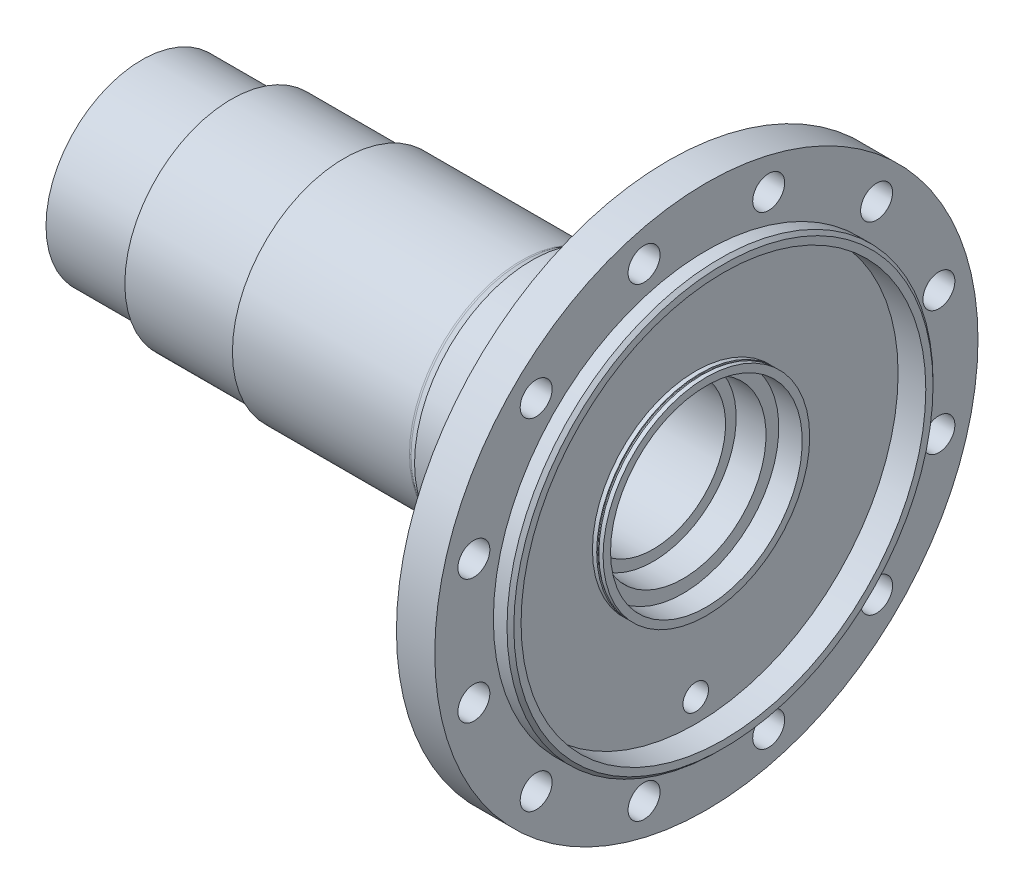
SolidWorks part; units mm, degrees
ref_plane "Спереди" through (0, 0, 0) normal (0, 0, 1) x (1, 0, 0)
ref_plane "Сверху" through (0, 0, 0) normal (0, 1, 0) x (1, 0, 0)
ref_plane "Справа" through (0, 0, 0) normal (1, 0, 0) x (0, 0, -1)
sketch "Эскиз1" plane through (0, 0, 0) normal (0, 0, 1) x (1, 0, 0)
  line L0 (0, 0) -> (273, 0)
  line L1 (0, 0) -> (0, 45)
  line L2 (0, 45) -> (42, 45)
  line L3 (42, 45) -> (42, 50)
  line L4 (42, 50) -> (95, 50)
  line L5 (95, 50) -> (95, 52.5)
  line L6 (95, 52.5) -> (178.134, 52.5)
  line L7 (179.134, 52.7679) -> (183, 55)
  line L8 (183, 55) -> (213, 55)
  line L9 (215, 57) -> (215, 60.7679)
  line L10 (215, 60.7679) -> (218, 62.5)
  line L11 (218, 62.5) -> (237, 62.5)
  line L12 (239, 64.5) -> (239, 65.5)
  line L13 (239, 65.5) -> (240.4142, 66.9142)
  line L14 (241, 68.3284) -> (241, 78)
  line L15 (241, 78) -> (244.4142, 81.4142)
  line L16 (245, 82.8284) -> (245, 92)
  line L17 (245, 92) -> (246.4142, 93.4142)
  line L18 (247, 94.8284) -> (247, 127.5)
  line L19 (247, 127.5) -> (265, 127.5)
  line L20 (265, 127.5) -> (265, 100)
  line L21 (265, 100) -> (271.4, 100)
  line L22 (271.4, 100) -> (273, 98.4)
  line L23 (273, 98.4) -> (273, 0)
  arc A0 (178.134, 52.5) -> (179.134, 52.7679) centre (178.134, 54.5) ccw
  arc A1 (213, 55) -> (215, 57) centre (213, 57) ccw
  arc A2 (237, 62.5) -> (239, 64.5) centre (237, 64.5) ccw
  arc A3 (240.4142, 66.9142) -> (241, 68.3284) centre (239, 68.3284) ccw
  arc A4 (244.4142, 81.4142) -> (245, 82.8284) centre (243, 82.8284) ccw
  arc A5 (246.4142, 93.4142) -> (247, 94.8284) centre (245, 94.8284) ccw
revolve "Повернуть1" add sketch "Эскиз1" angle 360 about L0
sketch "Эскиз2" plane through (0, 0, 0) normal (0, 0, 1) x (1, 0, 0)
  line L0 (0, 0) -> (273, 0)
  line L1 (0, 0) -> (0, 32.7321)
  line L2 (0, 32.7321) -> (3, 31)
  line L3 (3, 31) -> (203.5, 31)
  line L4 (203.5, 31) -> (203.5, 34)
  line L5 (203.5, 34) -> (240, 34)
  line L6 (240, 34) -> (240, 39)
  line L7 (240, 39) -> (254, 39)
  line L8 (254, 39) -> (254, 45)
  line L9 (254, 45) -> (265, 45)
  line L10 (265, 45) -> (265, 95)
  line L11 (265, 95) -> (273, 95)
  line L12 (273, 95) -> (273, 0)
revolve "Вырез-Повернуть1" cut sketch "Эскиз2" angle 360 about L0
sketch "Эскиз3" plane through (0, 0, 0) normal (0, 0, 1) x (1, 0, 0)
  line L0 (0, 0) -> (273, 0) construction
  line L1 (260, 48.5) -> (262, 48.5)
  line L2 (262, 48.5) -> (262, 95)
  line L3 (262, 95) -> (260, 95)
  line L4 (260, 95) -> (260, 48.5)
revolve "Rear_recess_left" cut sketch "Эскиз3" angle 360 about L0
sketch "Эскиз4" plane through (0, 0, 0) normal (0, 0, 1) x (1, 0, 0)
  line L0 (0, 0) -> (273, 0) construction
  line L1 (263, 48) -> (263, 95)
  line L2 (263, 95) -> (262, 95)
  line L3 (262, 95) -> (262, 48)
  arc A0 (262, 48) -> (262.5, 47.5) centre (262.5, 48) ccw
  arc A1 (262.5, 47.5) -> (263, 48) centre (262.5, 48) ccw
revolve "Collar_groove_nominal" cut sketch "Эскиз4" angle 360 about L0
sketch "Эскиз5" plane through (0, 0, 0) normal (0, 0, 1) x (1, 0, 0)
  line L0 (0, 0) -> (273, 0) construction
  line L1 (263, 48.5) -> (265, 48.5)
  line L2 (265, 48.5) -> (265, 95)
  line L3 (265, 95) -> (263, 95)
  line L4 (263, 95) -> (263, 48.5)
revolve "Rear_recess_lip" cut sketch "Эскиз5" angle 360 about L0
sketch "Эскиз6" plane through (0, 0, 0) normal (1, 0, 0) x (0, 0, -1)
  circle A0 centre (109.1496, 29.2466) radius 7.5
extrude "Вырез-Вытянуть1" cut sketch "Эскиз6" along normal through all
sketch "Эскиз7" plane through (0, 0, 0) normal (1, 0, 0) x (0, 0, -1)
  circle A0 centre (79.9031, 79.9031) radius 7.5
extrude "Вырез-Вытянуть2" cut sketch "Эскиз7" along normal through all
sketch "Эскиз8" plane through (0, 0, 0) normal (1, 0, 0) x (0, 0, -1)
  circle A0 centre (29.2466, 109.1496) radius 7.5
extrude "Вырез-Вытянуть3" cut sketch "Эскиз8" along normal through all
sketch "Эскиз9" plane through (0, 0, 0) normal (1, 0, 0) x (0, 0, -1)
  circle A0 centre (-29.2466, 109.1496) radius 7.5
extrude "Вырез-Вытянуть4" cut sketch "Эскиз9" along normal through all
sketch "Эскиз10" plane through (0, 0, 0) normal (1, 0, 0) x (0, 0, -1)
  circle A0 centre (-79.9031, 79.9031) radius 7.5
extrude "Вырез-Вытянуть5" cut sketch "Эскиз10" along normal through all
sketch "Эскиз11" plane through (0, 0, 0) normal (1, 0, 0) x (0, 0, -1)
  circle A0 centre (-109.1496, 29.2466) radius 7.5
extrude "Вырез-Вытянуть6" cut sketch "Эскиз11" along normal through all
sketch "Эскиз12" plane through (0, 0, 0) normal (1, 0, 0) x (0, 0, -1)
  circle A0 centre (-109.1496, -29.2466) radius 7.5
extrude "Вырез-Вытянуть7" cut sketch "Эскиз12" along normal through all
sketch "Эскиз13" plane through (0, 0, 0) normal (1, 0, 0) x (0, 0, -1)
  circle A0 centre (-79.9031, -79.9031) radius 7.5
extrude "Вырез-Вытянуть8" cut sketch "Эскиз13" along normal through all
sketch "Эскиз14" plane through (0, 0, 0) normal (1, 0, 0) x (0, 0, -1)
  circle A0 centre (-29.2466, -109.1496) radius 7.5
extrude "Вырез-Вытянуть9" cut sketch "Эскиз14" along normal through all
sketch "Эскиз15" plane through (0, 0, 0) normal (1, 0, 0) x (0, 0, -1)
  circle A0 centre (29.2466, -109.1496) radius 7.5
extrude "Вырез-Вытянуть10" cut sketch "Эскиз15" along normal through all
sketch "Эскиз16" plane through (0, 0, 0) normal (1, 0, 0) x (0, 0, -1)
  circle A0 centre (79.9031, -79.9031) radius 7.5
extrude "Вырез-Вытянуть11" cut sketch "Эскиз16" along normal through all
sketch "Эскиз17" plane through (0, 0, 0) normal (1, 0, 0) x (0, 0, -1)
  circle A0 centre (109.1496, -29.2466) radius 7.5
extrude "Вырез-Вытянуть12" cut sketch "Эскиз17" along normal through all
sketch "Эскиз18" plane through (0, 0, 0) normal (1, 0, 0) x (0, 0, -1)
  circle A0 centre (0, -84) radius 6
extrude "Вырез-Вытянуть13" cut sketch "Эскиз18" along normal through all
